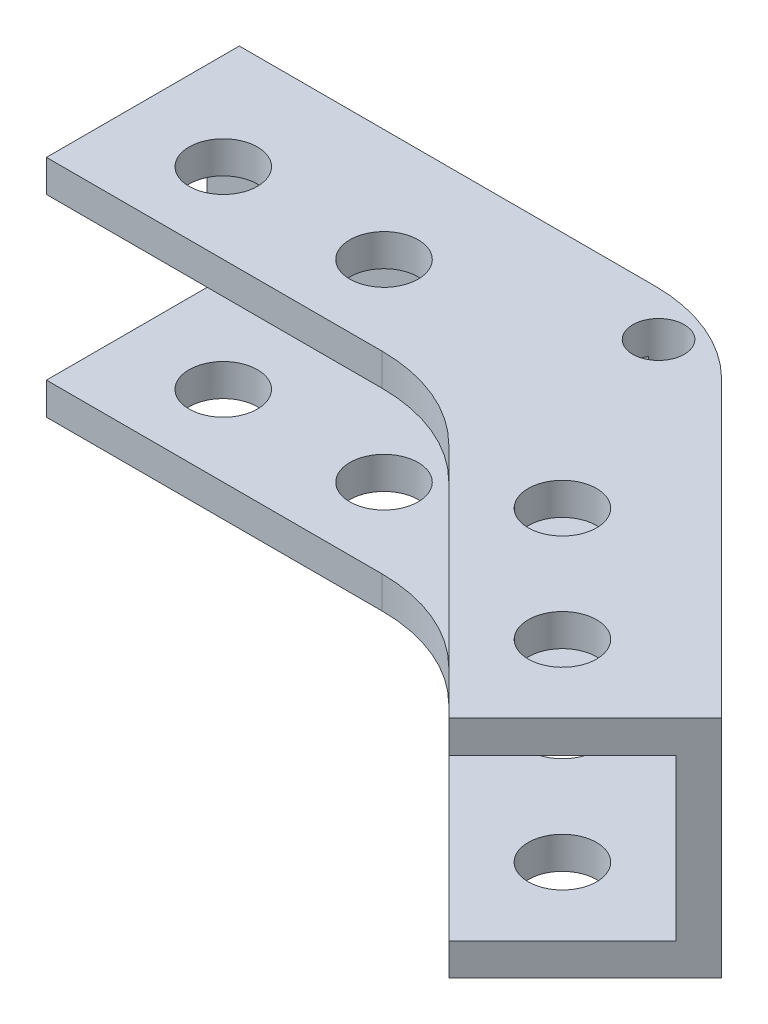
SolidWorks part; units mm, degrees
ref_plane "Front Plane" through (0, 0, 0) normal (0, 0, 1) x (1, 0, 0)
ref_plane "Top Plane" through (0, 0, 0) normal (0, 1, 0) x (1, 0, 0)
ref_plane "Right Plane" through (0, 0, 0) normal (1, 0, 0) x (0, 0, -1)
sketch "Sketch1" plane through (0, 0, 0) normal (0, 1, 0) x (1, 0, 0)
  line L0 (-27.1842, 10) -> (2.8158, 10)
  line L1 (2.8158, 10) -> (24.029, -11.2132)
  line L2 (24.029, -11.2132) -> (22.6148, -12.6274)
  line L3 (22.6148, -12.6274) -> (1.9874, 8)
  line L4 (1.9874, 8) -> (-27.1842, 8)
  line L5 (-27.1842, 8) -> (-27.1842, 10)
  dimension "D1" = 225
  dimension "D2" = 2
  dimension "D3" = 2
  dimension "D4" = 30
  dimension "D5" = 30
extrude "Boss-Extrude1" add sketch "Sketch1" along normal blind 14
sketch "Sketch2" plane through (0, 14, 0) normal (0, 1, 0) x (1, 0, 0)
  line L0 (-27.1842, 8) -> (-27.1842, -2)
  line L1 (-27.1842, -2) -> (-2.1547, -2)
  line L2 (-2.1547, -2) -> (15.5437, -19.6985)
  line L3 (15.5437, -19.6985) -> (22.6148, -12.6274)
  line L4 (22.6148, -12.6274) -> (1.9874, 8)
  line L5 (1.9874, 8) -> (-27.1842, 8)
  dimension "D1" = 10
  dimension "D2" = 10
extrude "Boss-Extrude2" add sketch "Sketch2" against normal blind 2
sketch "Sketch3" plane through (0, 0, 0) normal (0, -1, 0) x (1, 0, 0)
  line L0 (-27.1842, -8) -> (-27.1842, 2)
  line L1 (-27.1842, 2) -> (-2.1547, 2)
  line L2 (-2.1547, 2) -> (15.5437, 19.6985)
  line L3 (15.5437, 19.6985) -> (22.6148, 12.6274)
  line L4 (22.6148, 12.6274) -> (1.9874, -8)
  line L5 (1.9874, -8) -> (-27.1842, -8)
extrude "Boss-Extrude3" add sketch "Sketch3" against normal blind 2
sketch "Sketch4" plane through (0, 14, 0) normal (0, 1, 0) x (1, 0, 0)
  line L0 (2.8158, 10) -> (-27.1842, 10) construction
  line L1 (-27.1842, 10) -> (-27.1842, -2) construction
  line L2 (24.029, -11.2132) -> (2.8158, 10) construction
  line L3 (15.5437, -19.6985) -> (24.029, -11.2132) construction
  circle A0 centre (-21.1842, 3) radius 2.125
  circle A1 centre (-11.1842, 3) radius 2.125
  circle A2 centre (7.7656, -4.8492) radius 2.125
  circle A3 centre (14.8366, -11.9203) radius 2.125
  dimension "D1" = 4.25
  dimension "D2" = 4.25
  dimension "D3" = 4.25
  dimension "D4" = 4.25
  dimension "D5" = 7
  dimension "D6" = 7
  dimension "D7" = 6
  dimension "D8" = 16
  dimension "D9" = 7
  dimension "D10" = 7
  dimension "D11" = 6
  dimension "D12" = 16
extrude "Cut-Extrude1" cut sketch "Sketch4" against normal blind 15
sketch "Sketch5" plane through (0, 14, 0) normal (0, 1, 0) x (1, 0, 0)
  line L0 (2.8158, 10) -> (-2.1547, -2) construction
  circle A0 centre (1.6678, 7.2284) radius 1.6
  dimension "D2" = 3.2
  dimension "D1" = 3
extrude "Cut-Extrude2" cut sketch "Sketch5" against normal blind 15
sketch "Sketch6" plane through (0, 0, -10) normal (0, 0, -1) x (-1, 0, 0)
  line L0 (-2.8158, 14) -> (-2.8158, 0) construction
  line L1 (-2.8158, 10) -> (4.1842, 10)
  line L2 (-2.8158, 10) -> (-2.8158, 4)
  line L3 (-2.8158, 4) -> (4.1842, 4)
  line L4 (4.1842, 10) -> (4.1842, 4)
  line L5 (-2.8158, 14) -> (27.1842, 14) construction
  dimension "D1" = 6
  dimension "D2" = 0
  dimension "D3" = 7
  dimension "D4" = 4
extrude "Cut-Extrude3" cut sketch "Sketch6" against normal blind 15
sketch "Sketch7" plane through (6.4079, 0, -6.4079) normal (0.7071, 0, -0.7071) x (-0.7071, 0, -0.7071)
  line L0 (-24.92, 0) -> (5.08, 0) construction
  line L1 (5.08, 10) -> (-1.92, 10)
  line L2 (5.08, 10) -> (5.08, 4)
  line L3 (5.08, 4) -> (-1.92, 4)
  line L4 (-1.92, 10) -> (-1.92, 4)
  dimension "D1" = 7
  dimension "D2" = 4
extrude "Cut-Extrude4" cut sketch "Sketch7" against normal blind 15
fillet "Fillet2" radius 10 2 edges at (2.8158, 2, -10) (2.8158, 12, -10)
fillet "Fillet3" radius 10 2 edges at (-2.1547, 1, 2) (-2.1547, 13, 2)
